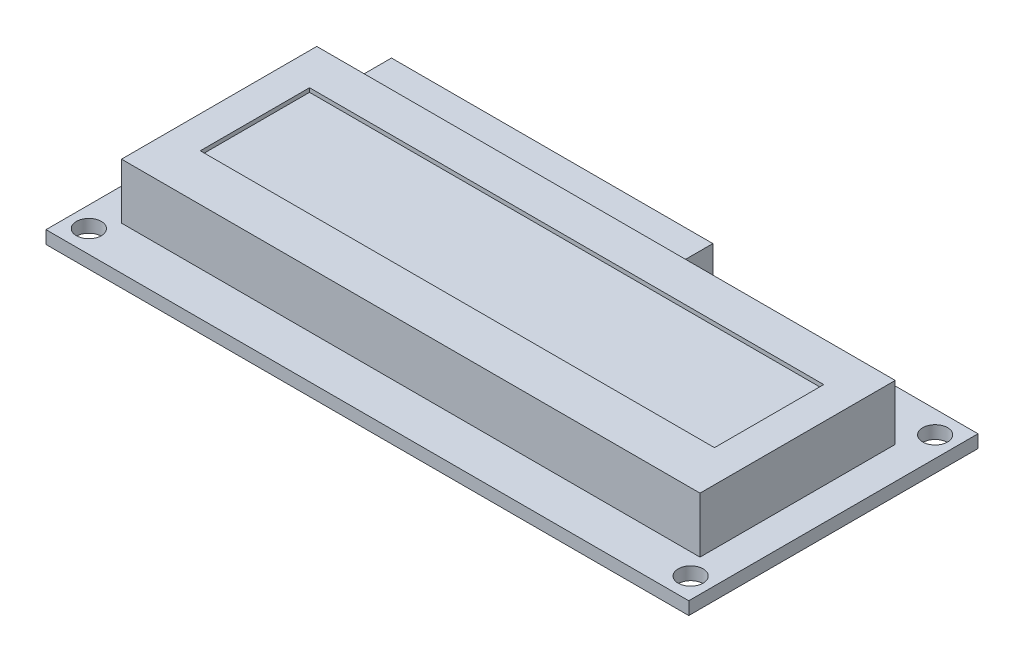
SolidWorks part; units mm, degrees
ref_plane "Front Plane" through (0, 0, 0) normal (0, 0, 1) x (1, 0, 0)
ref_plane "Top Plane" through (0, 0, 0) normal (0, 1, 0) x (1, 0, 0)
ref_plane "Right Plane" through (0, 0, 0) normal (1, 0, 0) x (0, 0, -1)
sketch "Sketch1" plane through (0, 0, 0) normal (0, 1, 0) x (1, 0, 0)
  line L1 (-40, -18) -> (40, -18)
  line L2 (-40, -18) -> (-40, 18)
  line L3 (-40, 18) -> (40, 18)
  line L4 (40, -18) -> (40, 18)
  line L5 (-40, -18) -> (40, 18) construction
  line L6 (-40, 18) -> (40, -18) construction
  point P0 (0, 0)
  dimension "D1" = 80
  dimension "D2" = 36
extrude "Boss-Extrude1" add sketch "Sketch1" along normal blind 1.6
sketch "Sketch2" plane through (0, 1.6, 0) normal (0, 1, 0) x (1, 0, 0)
  line L0 (40, 18) -> (-40, 18) construction
  line L1 (-36, -12.6) -> (36, -12.6)
  line L2 (-36, -12.6) -> (-36, 11.7)
  line L3 (-36, 11.7) -> (36, 11.7)
  line L4 (36, -12.6) -> (36, 11.7)
  line L5 (-36, -12.6) -> (36, 11.7) construction
  line L6 (-36, 11.7) -> (36, -12.6) construction
  line L7 (40, -18) -> (40, 18) construction
  point P0 (0, -0.45)
  dimension "D1" = 6.3
  dimension "D2" = 24.3
  dimension "D3" = 4
extrude "Boss-Extrude2" add sketch "Sketch2" along normal blind 6.9
sketch "Sketch3" plane through (0, 8.5, 0) normal (0, 1, 0) x (1, 0, 0)
  line L1 (-32, -6.8) -> (32, -6.8)
  line L2 (-32, -6.8) -> (-32, 6.8)
  line L3 (-32, 6.8) -> (32, 6.8)
  line L4 (32, -6.8) -> (32, 6.8)
  line L5 (-32, -6.8) -> (32, 6.8) construction
  line L6 (-32, 6.8) -> (32, -6.8) construction
  point P0 (0, 0)
  dimension "D1" = 13.6
  dimension "D2" = 64
extrude "Cut-Extrude1" cut sketch "Sketch3" against normal blind 0.5
sketch "Sketch5" plane through (0, 1.6, 0) normal (0, 1, 0) x (1, 0, 0)
  line L0 (40, 18) -> (-40, 18) construction
  line L1 (-33, 18) -> (7, 18)
  line L2 (-33, 18) -> (-33, 14)
  line L3 (-33, 14) -> (7, 14)
  line L4 (7, 18) -> (7, 14)
  line L5 (-40, 18) -> (-40, -18) construction
  dimension "D1" = 40
  dimension "D2" = 7
  dimension "D3" = 4
extrude "Boss-Extrude3" add sketch "Sketch5" along normal blind 4 and the other way blind 7
sketch "Sketch7" plane through (0, 1.6, 0) normal (0, 1, 0) x (1, 0, 0)
  line L0 (-37.45, 16.7663) -> (-37.45, 17.7663) construction
  line L2 (-39, 15.2163) -> (-40, 15.2163) construction
  line L3 (-40, 18) -> (-40, -18) construction
  line L4 (0, 0) -> (0, 18) construction
  line L5 (7, 18) -> (-33, 18) construction
  line L6 (0, 0) -> (-40, 0) construction
  circle A0 centre (-37.45, 15.2163) radius 1.55
  circle A1 centre (37.45, 15.2163) radius 1.55
  circle A2 centre (37.45, -15.2163) radius 1.55
  circle A3 centre (-37.45, -15.2163) radius 1.55
  dimension "D1" = 3.1
  dimension "D2" = 1
extrude "Cut-Extrude2" cut sketch "Sketch7" against normal through all
sketch "Sketch8" plane through (0, 0, -14) normal (0, 0, 1) x (1, 0, 0)
  line L1 (-33, 0) -> (7, 0)
  line L2 (-33, 0) -> (-33, -5.4)
  line L3 (-33, -5.4) -> (7, -5.4)
  line L4 (7, 0) -> (7, -5.4)
extrude "Boss-Extrude4" add sketch "Sketch8" along normal blind 10
